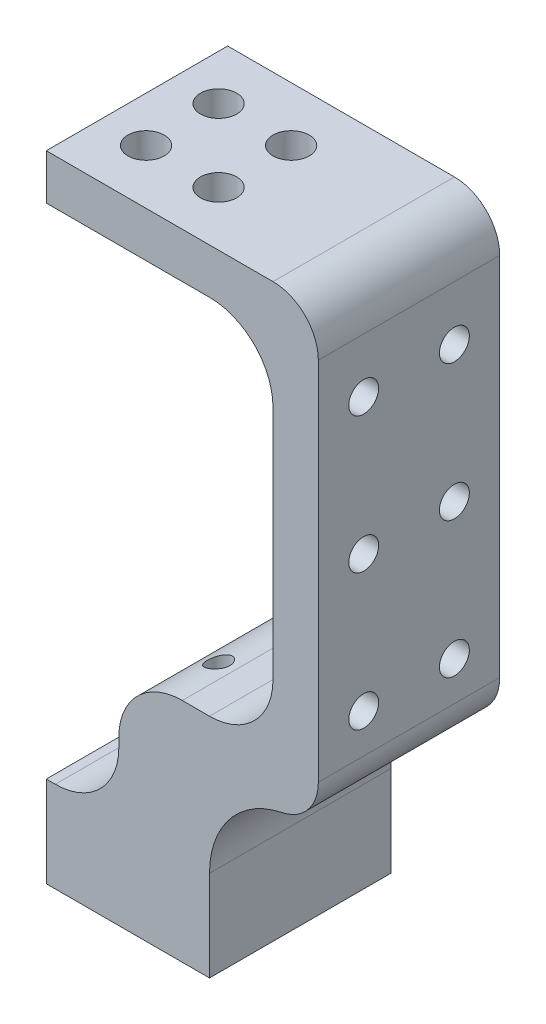
SolidWorks part; units mm, degrees
material "6061 Alloy"
ref_plane "Front Plane" through (0, 0, 0) normal (0, 0, 1) x (1, 0, 0)
ref_plane "Top Plane" through (0, 0, 0) normal (0, 1, 0) x (1, 0, 0)
ref_plane "Right Plane" through (0, 0, 0) normal (1, 0, 0) x (0, 0, -1)
sketch "Sketch1" plane through (0, 0, 0) normal (1, 0, 0) x (0, 0, -1)
  line L1 (-10, -35) -> (10, -35)
  line L2 (-10, -35) -> (-10, 35)
  line L3 (-10, 35) -> (10, 35)
  line L4 (10, -35) -> (10, 35)
  line L5 (-10, -35) -> (10, 35) construction
  line L6 (-10, 35) -> (10, -35) construction
  point P0 (0, 0)
  dimension "D1" = 70
  dimension "D2" = 20
extrude "Boss-Extrude1" add sketch "Sketch1" along normal blind 30
sketch "Sketch2" plane through (0, 0, 10) normal (0, 0, 1) x (1, 0, 0)
  line L0 (30, 35) -> (0, 35) construction
  line L1 (30, -35) -> (18, -35)
  line L2 (30, -35) -> (30, -15)
  line L3 (30, -15) -> (18, -15)
  line L4 (18, -35) -> (18, -15)
  line L5 (0, 35) -> (0, -35) construction
  dimension "D1" = 50
  dimension "D2" = 18
extrude "Cut-Extrude1" cut sketch "Sketch2" against normal through all
fillet "Fillet1" radius 10 1 edges at (18, -15, 0)
fillet "Fillet2" radius 5 2 edges at (30, 35, 0) (30, -15, 0)
sketch "Sketch6" plane through (0, 0, 10) normal (0, 0, 1) x (1, 0, 0)
  line L0 (0, 30) -> (25, 30)
  line L1 (0, 35) -> (0, -35) construction
  line L2 (25, 30) -> (25, -10)
  line L3 (25, -10) -> (8, -10)
  line L4 (8, -10) -> (8, -25)
  line L5 (8, -25) -> (0, -25)
  line L6 (0, -25) -> (0, 30)
  line L7 (18, -25) -> (18, -35) construction
  line L8 (18, -35) -> (0, -35) construction
  line L9 (30, 30) -> (30, -10.3031) construction
  line L10 (25, 35) -> (0, 35) construction
  dimension "D1" = 10
  dimension "D2" = 10
  dimension "D3" = 5
  dimension "D4" = 25
  dimension "D5" = 5
extrude "Cut-Extrude2" cut sketch "Sketch6" against normal through all
fillet "Fillet3" radius 7 3 edges at (8, -25, 0) (25, 30, 0) (25, -10, 0)
fillet "Fillet4" radius 7 1 edges at (8, -10, 0)
hole_wizard "Ø4.0 Reamed hole" positions "Sketch4" profile "Sketch5" hole size "Ø4.0" standard "ANSI Metric"
sketch "Sketch4" plane through (0, 35, 0) normal (0, 1, 0) x (1, 0, 0)
  line L1 (13, 4) -> (5, 4)
  line L2 (13, 4) -> (13, -4)
  line L3 (13, -4) -> (5, -4)
  line L4 (5, 4) -> (5, -4)
  line L5 (13, 4) -> (5, -4) construction
  line L6 (13, -4) -> (5, 4) construction
  line L7 (0, 0) -> (30, 0) construction
  line L8 (0, 10) -> (0, -10) construction
  line L9 (30, 10) -> (30, -10) construction
  point P0 (5, -4)
  point P2 (5, 4)
  point P4 (13, 4)
  point P6 (13, -4)
  point P82 (9, 0)
  dimension "D1" = 8
  dimension "D2" = 17
sketch "Sketch5" plane through (5, 35, 4) normal (1, 0, 0) x (0, 0, 1)
  line L0 (0, 0) -> (0, 5)
  line L1 (0, 5) -> (2, 5)
  line L2 (2, 5) -> (2, 0)
  line L5 (2, 0) -> (0, 0)
  line L11 (0, -6.35) -> (0, 107.95) construction
  dimension "Thru Hole Dia." = 4
  dimension "Thru Hole Depth" = 5
hole_wizard "M3x0.5 Tapped Hole1" positions "Sketch8" profile "Sketch9" tap size "M3x0.5" standard "ANSI Metric"
sketch "Sketch8" plane through (0, -35, 0) normal (0, -1, 0) x (-1, 0, 0)
  point P0 (-5, -4)
  point P2 (-13, -4)
  point P4 (-5, 4)
  point P6 (-13, 4)
sketch "Sketch9" plane through (5, -35, 4) normal (1, 0, 0) x (0, 0, -1)
  line L0 (0, 0) -> (0, 11.2554)
  line L1 (0, 11.2554) -> (1.25, 11.2554)
  line L2 (1.25, 11.2554) -> (1.25, 0)
  line L5 (1.25, 0) -> (0, 0)
  line L11 (0, -6.35) -> (0, 107.95) construction
  dimension "Thru Tap Drill Dia." = 2.5
  dimension "Thru Tap Drill Depth" = 11.2554
cosmetic thread "Hole Thread1" parameters "D2"=3
cosmetic thread "Hole Thread2" parameters "D2"=3
cosmetic thread "Hole Thread3" parameters "D2"=3
cosmetic thread "Hole Thread4" parameters "D2"=3
hole_wizard "Ø4.0 Reamed hole, bottom" positions "Sketch11" profile "Sketch12" hole size "Ø4.0" standard "ANSI Metric"
sketch "Sketch11" plane through (0, -35, 0) normal (0, -1, 0) x (-1, 0, 0)
  point P0 (-5, -4)
  point P2 (-13, -4)
  point P4 (-13, 4)
  point P6 (-5, 4)
sketch "Sketch12" plane through (5, -35, 4) normal (1, 0, 0) x (0, 0, -1)
  line L0 (0, 0) -> (0, 6.2017)
  line L1 (0, 6.2017) -> (2, 5)
  line L2 (2, 5) -> (2, 0)
  line L5 (2, 0) -> (0, 0)
  line L10 (0, 6.2017) -> (-2, 5) construction
  line L11 (0, -6.35) -> (0, 107.95) construction
  dimension "Hole Dia." = 4
  dimension "Hole Depth" = 5
  dimension "Drill Angle" = 118
hole_wizard "M4x0.7 Tapped Hole1" positions "Sketch14" profile "Sketch15" tap size "M4x0.7" standard "ANSI Metric"
sketch "Sketch14" plane through (30, 0, 0) normal (1, 0, 0) x (0, 0, -1)
  line L12 (-5, 24) -> (5, 24) construction
  line L15 (-5, 9) -> (5, 9) construction
  line L18 (-5, -6) -> (5, -6) construction
  line L21 (0, -6) -> (0, 9) construction
  line L22 (0, 9) -> (0, 24) construction
  line L24 (10, 35) -> (-10, 35) construction
  line L25 (10, 30) -> (-10, 30) construction
  line L26 (11, 0) -> (-11, 0) construction
  point P136 (-5, 24)
  point P138 (5, 24)
  point P140 (-5, 9)
  point P142 (5, 9)
  point P144 (-5, -6)
  point P146 (5, -6)
  point P161 (0, 30)
  dimension "D1" = 30
  dimension "D2" = 10
  dimension "D3" = 9
sketch "Sketch15" plane through (30, 24, 5) normal (0, 1, 0) x (0, 0, -1)
  line L0 (0, 0) -> (0, 11.0914)
  line L1 (0, 11.0914) -> (1.65, 10.1)
  line L2 (1.65, 10.1) -> (1.65, 0)
  line L5 (1.65, 0) -> (0, 0)
  line L10 (0, 11.0914) -> (-1.65, 10.1) construction
  line L11 (0, -6.35) -> (0, 107.95) construction
  dimension "Tap Drill Dia." = 3.3
  dimension "Tap Drill Depth" = 10.1
  dimension "Drill Angle" = 118
cosmetic thread "Hole Thread5" parameters "D1"=6.3112, "D2"=4
cosmetic thread "Hole Thread6" parameters "D1"=6.3112, "D2"=4
cosmetic thread "Hole Thread7" parameters "D1"=5, "D2"=4
cosmetic thread "Hole Thread8" parameters "D1"=5, "D2"=4
cosmetic thread "Hole Thread9" parameters "D1"=5.7851, "D2"=4
cosmetic thread "Hole Thread10" parameters "D1"=5.7851, "D2"=4
